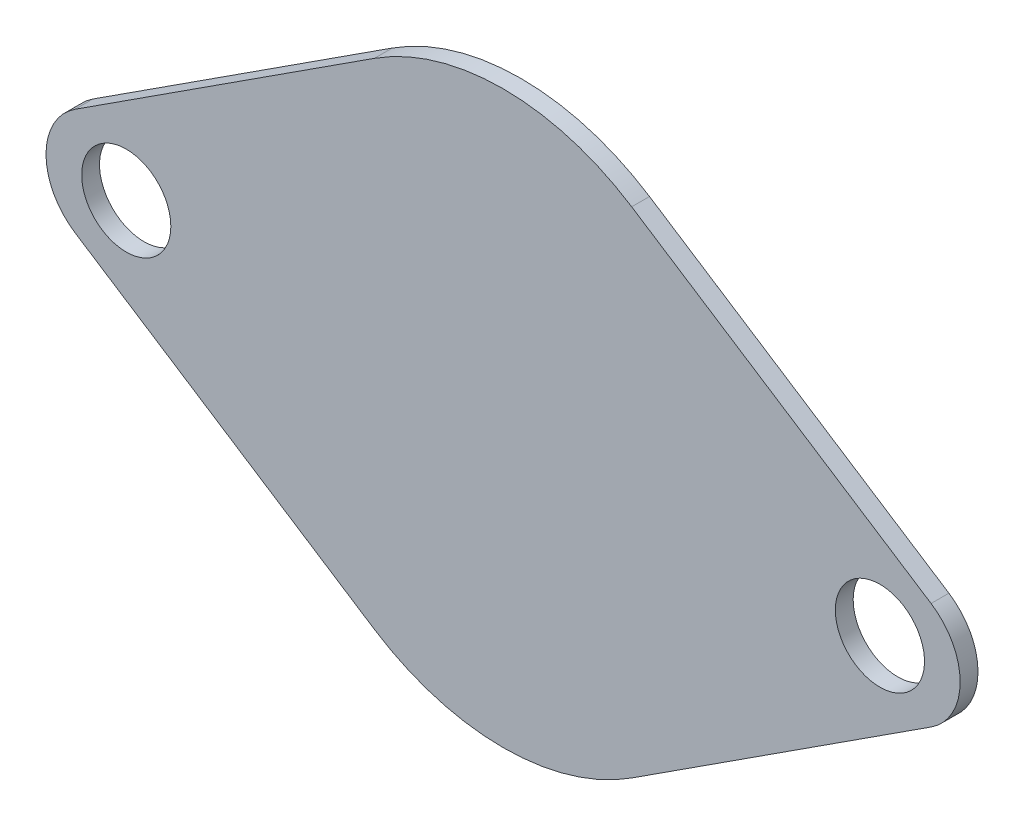
SolidWorks part; units mm, degrees
ref_plane "Plan de face" through (0, 0, 0) normal (0, 0, 1) x (1, 0, 0)
ref_plane "Plan de dessus" through (0, 0, 0) normal (0, 1, 0) x (1, 0, 0)
ref_plane "Plan de droite" through (0, 0, 0) normal (1, 0, 0) x (0, 0, -1)
sketch "Esquisse1" plane through (0, 0, 0) normal (0, 0, 1) x (1, 0, 0)
  line L0 (0, 0) -> (16.7886, 10.8694)
  line L1 (31.2114, 10.8694) -> (48, 0)
  line L2 (0, -6) -> (16.7886, -16.8694)
  line L3 (48, -6) -> (31.2114, -16.8694)
  line L4 (24, 13) -> (33.318, 13) construction
  line L5 (24, -19) -> (33.318, -19) construction
  line L6 (-1.6316, -3) -> (-1.6316, -0.2692) construction
  line L7 (24, 13) -> (24, -25.638) construction
  arc A0 (16.7886, 10.8694) -> (31.2114, 10.8694) centre (24, -0.2692) cw
  arc A1 (16.7886, -16.8694) -> (31.2114, -16.8694) centre (24, -5.7308) ccw
  arc A2 (0, 0) -> (0, -6) centre (1.9423, -3) ccw
  arc A3 (48, 0) -> (48, -6) centre (46.0577, -3) cw
  circle A4 centre (2.8684, -3) radius 2.5
  circle A5 centre (45.1316, -3) radius 2.5
  dimension "D9" = 5
  dimension "D1" = 20
  dimension "D2" = 20
  dimension "D3" = 20
  dimension "D4" = 20
  dimension "D5" = 6
  dimension "D6" = 48
  dimension "D7" = 32
  dimension "D8" = 4.5
  dimension "D10" = 3
extrude "Boss.-Extru.1" add sketch "Esquisse1" along normal blind 1
